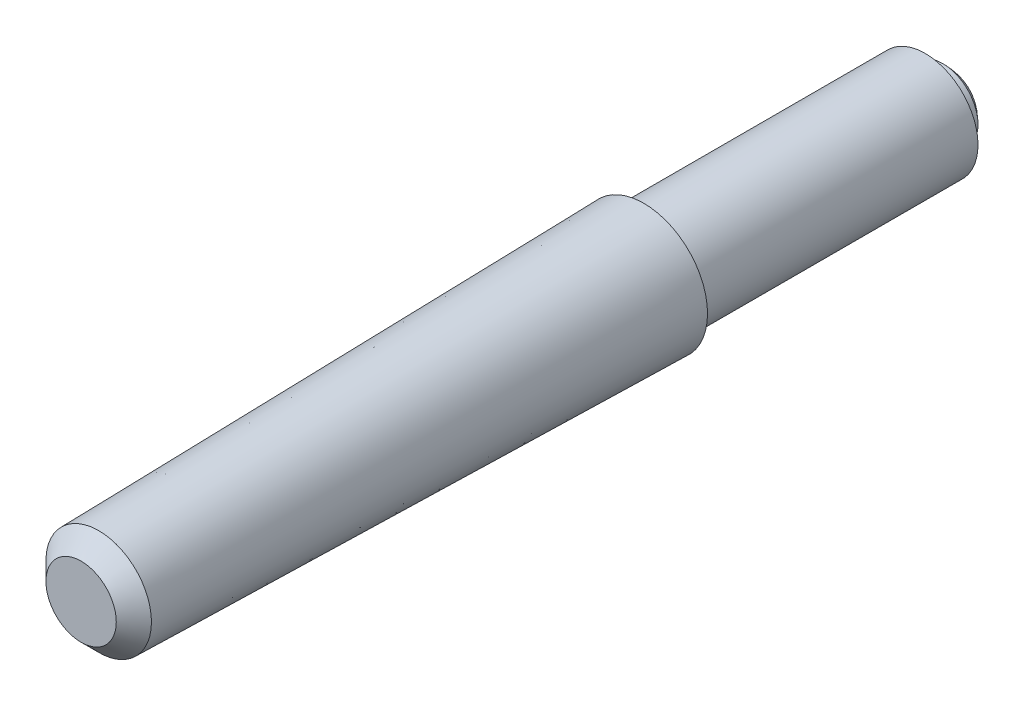
SolidWorks part; units mm, degrees
ref_plane "Спереди" through (0, 0, 0) normal (0, 0, 1) x (1, 0, 0)
ref_plane "Сверху" through (0, 0, 0) normal (0, 1, 0) x (1, 0, 0)
ref_plane "Справа" through (0, 0, 0) normal (1, 0, 0) x (0, 0, -1)
other "Configuration Table"
sketch "Эскиз1" plane through (0, 0, 0) normal (1, 0, 0) x (0, 0, -1)
  line L0 (-39.3582, 0) -> (10.6418, 0) construction
  line L1 (-39.3582, 0) -> (-39.3582, 2)
  line L2 (-38.3582, 3) -> (-7.3582, 3.62)
  line L3 (-7.3582, 3.62) -> (-7.3582, 3)
  line L4 (-7.3582, 3) -> (8.6418, 3)
  line L5 (8.6418, 3) -> (8.6418, 2)
  line L6 (8.6418, 2) -> (9.6418, 2)
  line L8 (-39.3582, 2) -> (-38.3582, 3)
  line L9 (-39.3582, 0) -> (10.6418, 0)
  spline S0 degree 2 poles (9.6418, 2) (10.6418, 1) (10.6418, 0) knots 0 0 0 0.5 0.5 0.5
  dimension "D1" = 1
  dimension "D2" = 50
  dimension "D3" = 2
  dimension "D4" = 39.3582
  dimension "D5" = 31
  dimension "D6" = 3.62
  dimension "D7" = 3
  dimension "D8" = 2
  dimension "D9" = 8.6418
  dimension "D10" = 7.3582
  dimension "D11" = 9.6418
revolve "Повернуть1" add sketch "Эскиз1" angle 360 about L0
cosmetic thread "Условное изображение резьбы1" parameters "D1"=12, "D2"=5
